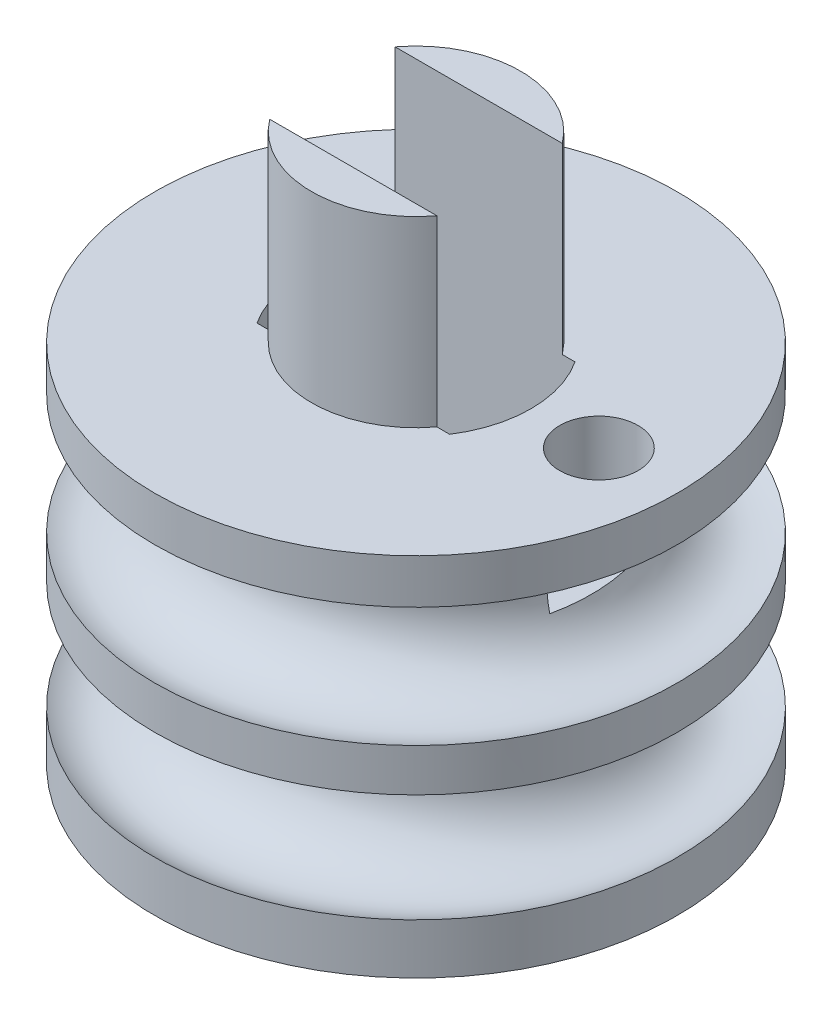
SolidWorks part; units mm, degrees
ref_plane "前视基准面" through (0, 0, 0) normal (0, 0, 1) x (1, 0, 0)
ref_plane "上视基准面" through (0, 0, 0) normal (0, 1, 0) x (1, 0, 0)
ref_plane "右视基准面" through (0, 0, 0) normal (1, 0, 0) x (0, 0, -1)
other "Configuration Table"
sketch "草图1" plane through (0, 0, 0) normal (0, 1, 0) x (1, 0, 0)
  circle A0 centre (0, 0) radius 2.75
  dimension "D1" = 5.5
extrude "凸台-拉伸1" add sketch "草图1" along normal blind 8
sketch "草图2" plane through (0, 8, 0) normal (0, 1, 0) x (1, 0, 0)
  line L0 (-1.8439, 1.2) -> (1.8439, 1.2)
  line L1 (-1.8439, -1.2) -> (1.8439, -1.2)
  circle A0 centre (0, 0) radius 2.2
  dimension "D1" = 4.4
  dimension "D2" = 2.4
extrude "切除-拉伸1" cut sketch "草图2" against normal offset from surface (7 mm away) 1 contours L1 A0 L0 up to face at (0, 0, 2.75)
sketch "草图4" plane through (0, 8, 0) normal (0, 1, 0) x (1, 0, 0)
  line L2 (1.6363, -1.15) -> (-1.6363, -1.15)
  line L3 (1.6363, 1.15) -> (-1.6363, 1.15)
  circle A0 centre (0, 0) radius 2
  circle A1 centre (0, 0) radius 2 construction
  circle A2 centre (0, 0) radius 2
  line M1 (1.8439, -1.2) -> (-1.8439, -1.2)
  line M3 (-1.8439, 1.2) -> (1.8439, 1.2)
  dimension "D1" = 4
  dimension "D2" = 2.3
extrude "凸台-拉伸2" add sketch "草图4" along normal blind 3.5 contours A0 M3 | A0 M1
sketch "草图5" plane through (0, 8, 0) normal (0, 1, 0) x (1, 0, 0)
  circle A0 centre (0, 0) radius 5
  circle A1 centre (0, 0) radius 2.75
  circle A2 centre (0, 0) radius 2.75
  dimension "D2" = 10
  dimension "D1" = 0
extrude "凸台-拉伸3" add sketch "草图5" against normal up to surface (8 mm away) up to face at (0, 0, 2.75)
ref_plane "基准面1" through (0, 4, 0) normal (0, -1, 0) x (-1, 0, 0)
ref_plane "基准面2" through (0, 3, 0) normal (0, -1, 0) x (-1, 0, 0)
ref_plane "基准面3" through (0, 6, 0) normal (0, 1, 0) x (1, 0, 0)
sketch "草图16" plane through (0, 3, 0) normal (0, -1, 0) x (-1, 0, 0)
  circle A0 centre (0, 0) radius 4.3
  circle A1 centre (0, 0) radius 5 construction
  dimension "D1" = 0.7
sweep "切除-扫描1" cut path "草图16" circular profile diameter 2.5 parameters "D3"=2.5
sketch "草图30" plane through (0, 6, 0) normal (0, 1, 0) x (1, 0, 0)
  circle A0 centre (0, 0) radius 4.5
  circle A1 centre (0, 0) radius 5 construction
  dimension "D1" = 0.5
sweep "切除-扫描2" cut path "草图30" circular profile diameter 2.5 parameters "D3"=2.5
sketch "草图43" plane through (0, 8, 0) normal (0, 1, 0) x (1, 0, 0)
  circle A0 centre (3.5, 0) radius 0.75
  dimension "D1" = 1.5
  dimension "D2" = 3.5
extrude "切除-拉伸2" cut sketch "草图43" against normal blind 2.5
sketch "草图47" plane through (0, 0, 0) normal (0, -1, 0) x (1, 0, 0)
  circle A0 centre (0, 0) radius 2.5
  circle A2 centre (0, 0) radius 5
  circle A3 centre (0, 0) radius 5
  circle M2 centre (0, 0) radius 5
  dimension "D1" = 5
  dimension "D2" = 0
extrude "切除-拉伸3" cut sketch "草图47" against normal blind 1 contours A0 M2
sketch "草图48" plane through (0, 1, 0) normal (0, -1, 0) x (1, 0, 0)
  circle A0 centre (-3.5, 0) radius 0.75
  circle A1 centre (0, 0) radius 5 construction
  dimension "D1" = 1.5
  dimension "D2" = 3.5
extrude "切除-拉伸4" cut sketch "草图48" against normal blind 2.5
